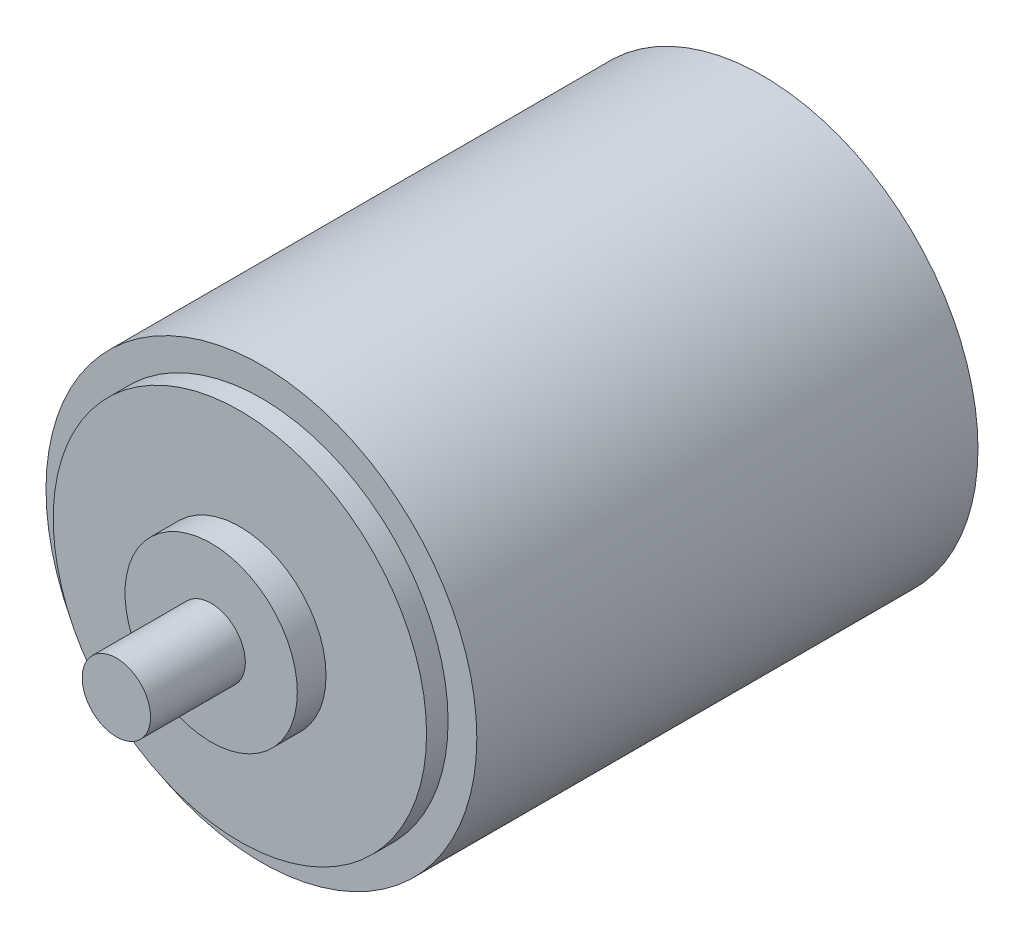
SolidWorks part; units mm, degrees
ref_plane "Plan de face" through (0, 0, 0) normal (0, 0, 1) x (1, 0, 0)
ref_plane "Plan de dessus" through (0, 0, 0) normal (0, 1, 0) x (1, 0, 0)
ref_plane "Plan de droite" through (0, 0, 0) normal (1, 0, 0) x (0, 0, -1)
sketch "Esquisse1" plane through (0, 0, 0) normal (0, 0, 1) x (1, 0, 0)
  circle A0 centre (0, 0) radius 7.5
  dimension "D1" = 15
extrude "Boss.-Extru.1" add sketch "Esquisse1" along normal blind 15.05
sketch "Esquisse3" plane through (0, 0, 15.05) normal (0, 0, 1) x (1, 0, 0)
  circle A0 centre (0, 0) radius 6.5
  dimension "D1" = 13
extrude "Boss.-Extru.2" add sketch "Esquisse3" along normal blind 0.75
sketch "Esquisse4" plane through (0, 0, 15.8) normal (0, 0, 1) x (1, 0, 0)
  circle A0 centre (0, 0) radius 3
  dimension "D1" = 6
extrude "Boss.-Extru.3" add sketch "Esquisse4" along normal blind 1
sketch "Esquisse5" plane through (0, 0, 16.8) normal (0, 0, 1) x (1, 0, 0)
  circle A0 centre (0, 0) radius 1.19
  dimension "D1" = 2.38
extrude "Boss.-Extru.4" add sketch "Esquisse5" along normal blind 3.3
sketch "Esquisse8" plane through (0, 0, 0) normal (0, 0, -1) x (-1, 0, 0)
  line L1 (-4.755, -5.8) -> (4.755, -5.8)
  arc A0 (4.755, -5.8) -> (-4.755, -5.8) centre (0, 0) ccw
extrude "Boss.-Extru.7" add sketch "Esquisse8" along normal blind 2.4
